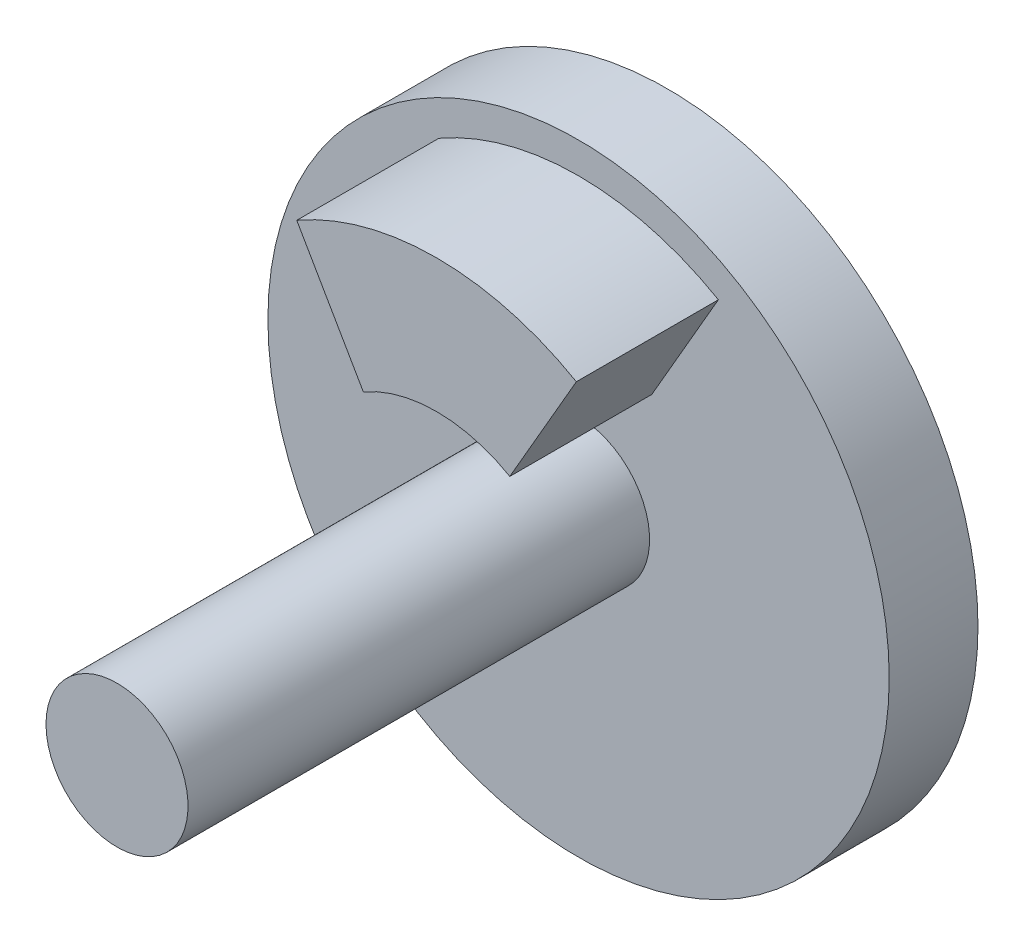
SolidWorks part; units mm, degrees
ref_plane "Front Plane" through (0, 0, 0) normal (0, 0, 1) x (1, 0, 0)
ref_plane "Top Plane" through (0, 0, 0) normal (0, 1, 0) x (1, 0, 0)
ref_plane "Right Plane" through (0, 0, 0) normal (1, 0, 0) x (0, 0, -1)
sketch "Sketch1" plane through (0, 0, 0) normal (0, 0, 1) x (1, 0, 0)
  circle A0 centre (0, 0) radius 17.5
  dimension "D1" = 35
extrude "Boss-Extrude1" add sketch "Sketch1" along normal mid plane 5
sketch "Sketch2" plane through (0, 0, 2.5) normal (0, 0, 1) x (1, 0, 0)
  line L3 (0, 0) -> (0, 11) construction
  line L4 (7.875, 13.6399) -> (4.125, 7.1447)
  line L5 (-4.125, 7.1447) -> (-7.875, 13.6399)
  arc A1 (4.125, 7.1447) -> (-4.125, 7.1447) centre (0, 0) ccw
  arc A6 (-7.875, 13.6399) -> (7.875, 13.6399) centre (0, 0) cw
  circle A7 centre (0, 0) radius 17.5 construction
  dimension "D2" = 7.5
  dimension "D3" = 1.75
  dimension "D1" = 30
extrude "Boss-Extrude2" add sketch "Sketch2" along normal blind 8
sketch "Sketch3" plane through (0, 0, 2.5) normal (0, 0, 1) x (1, 0, 0)
  circle A0 centre (0, 0) radius 4
extrude "Boss-Extrude3" add sketch "Sketch3" along normal blind 26
sketch "Sketch4" plane through (0, 0, -2.5) normal (0, 0, -1) x (-1, 0, 0)
  line L2 (-2.3851, 2.2) -> (2.3851, 2.2)
  arc A2 (-2.3851, 2.2) -> (2.3851, 2.2) centre (0, 0) ccw
extrude "Cut-Extrude1" cut sketch "Sketch4" against normal blind 10
